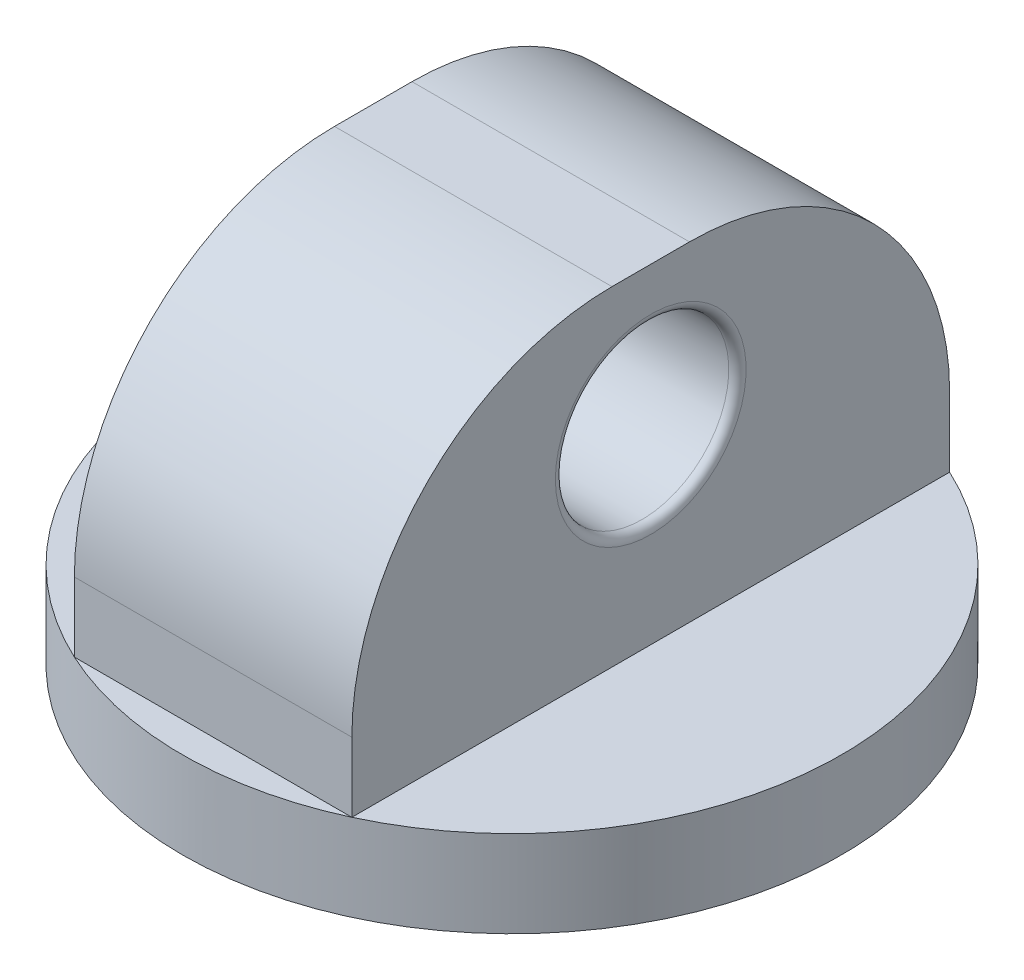
SolidWorks part; units mm, degrees
ref_plane "Front Plane" through (0, 0, 0) normal (0, 0, 1) x (1, 0, 0)
ref_plane "Top Plane" through (0, 0, 0) normal (0, 1, 0) x (1, 0, 0)
ref_plane "Right Plane" through (0, 0, 0) normal (1, 0, 0) x (0, 0, -1)
sketch "Sketch1" plane through (0, 0, 0) normal (0, 1, 0) x (1, 0, 0)
  circle A0 centre (0, 0) radius 38
  dimension "D1" = 76
extrude "Boss-Extrude1" add sketch "Sketch1" along normal blind 10
sketch "Sketch2" plane through (0, 10, 0) normal (0, 1, 0) x (1, 0, 0)
  line L1 (-16, 34.4674) -> (16, 34.4674)
  line L2 (-16, 34.4674) -> (-16, -34.4674)
  line L3 (-16, -34.4674) -> (16, -34.4674)
  line L4 (16, 34.4674) -> (16, -34.4674)
  line L5 (-16, 34.4674) -> (16, -34.4674) construction
  line L6 (-16, -34.4674) -> (16, 34.4674) construction
  circle A0 centre (0, 0) radius 38 construction
  point P0 (0, 0)
  dimension "D1" = 32
extrude "Boss-Extrude2" add sketch "Sketch2" along normal blind 38
sketch "Sketch3" plane through (0, 0, 0) normal (1, 0, 0) x (0, 0, -1)
  line L0 (-34.4674, 10) -> (34.4674, 10) construction
  circle A0 centre (0, 32) radius 10
  dimension "D1" = 20
  dimension "D2" = 22
extrude "Cut-Extrude1" cut sketch "Sketch3" against normal blind 38 and the other way blind 38
fillet "Fillet3" radius 30 2 edges at (0, 48, -34.4674) (0, 48, 34.4674)
fillet "Fillet6" radius 1 2 edges at (-16, 32, -10) (16, 32, 10)
